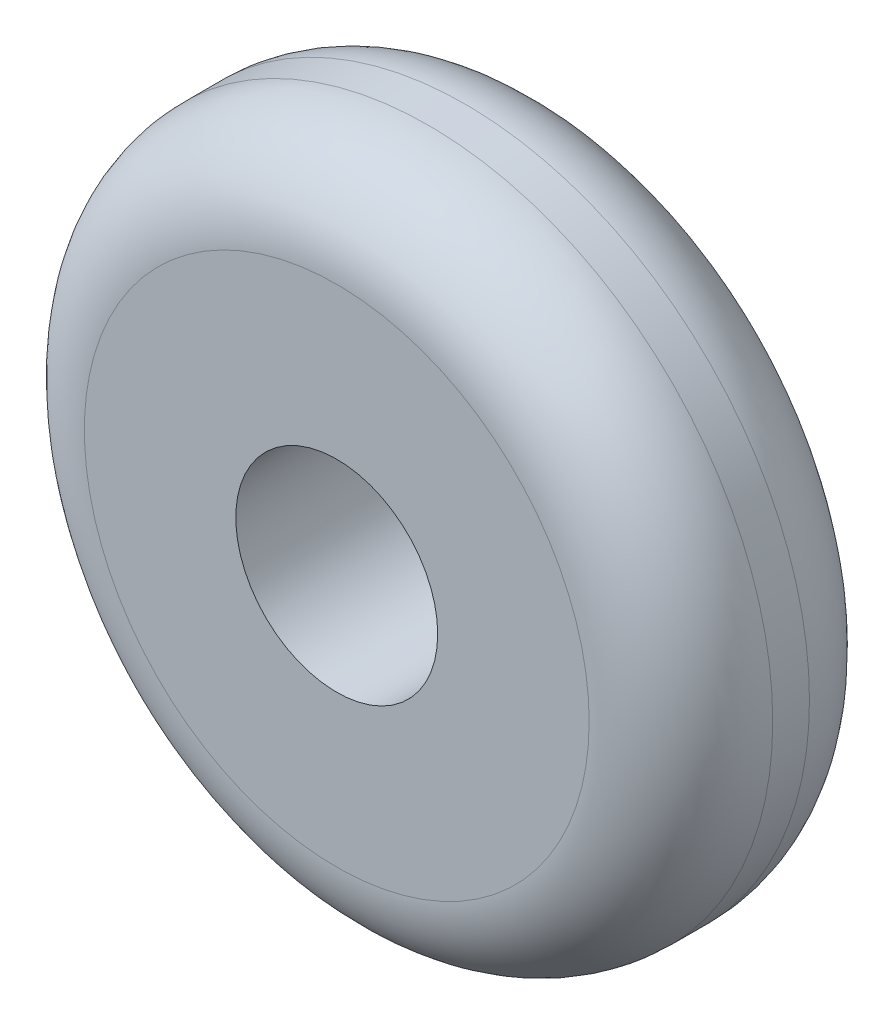
SolidWorks part; units mm, degrees
ref_plane "前视基准面" through (0, 0, 0) normal (0, 0, 1) x (1, 0, 0)
ref_plane "上视基准面" through (0, 0, 0) normal (0, 1, 0) x (1, 0, 0)
ref_plane "右视基准面" through (0, 0, 0) normal (1, 0, 0) x (0, 0, -1)
other "Configuration Table"
sketch "草图1" plane through (0, 0, 0) normal (0, 0, 1) x (1, 0, 0)
  circle A0 centre (0, 0) radius 37.5
  circle A1 centre (0, 0) radius 11
  dimension "D1" = 75
  dimension "D2" = 22
extrude "凸台-拉伸1" add sketch "草图1" along normal blind 24
fillet "圆角1" radius 10 2 edges at (37.5, 0, 0) (37.5, 0, 24)
ref_plane "基准面1" through (0, 0, 12) normal (0, 0, 1) x (1, 0, 0)
